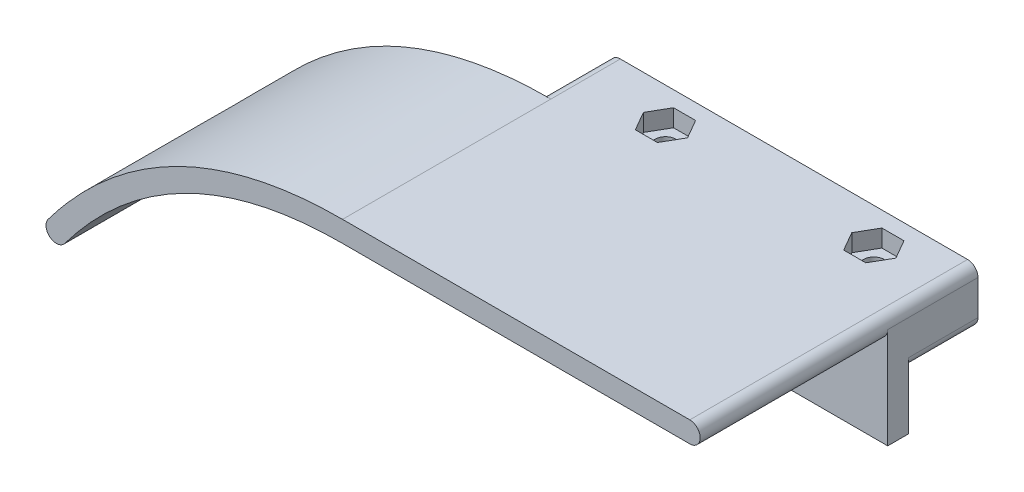
SolidWorks part; units mm, degrees
material "ABS"
ref_plane "前视基准面" through (0, 0, 0) normal (0, 0, 1) x (1, 0, 0)
ref_plane "上视基准面" through (0, 0, 0) normal (0, 1, 0) x (1, 0, 0)
ref_plane "右视基准面" through (0, 0, 0) normal (1, 0, 0) x (0, 0, -1)
sketch "草图1" plane through (0, 0, 0) normal (0, 0, 1) x (1, 0, 0)
  line L0 (-25, -1.5) -> (-50, -1.5) construction
  line L1 (-25, -1.5) -> (25, -1.5)
  line L2 (-25, -1.5) -> (-25, 1.5) construction
  line L4 (25, -1.5) -> (25, 1.5) construction
  line L5 (-25, -1.5) -> (25, 1.5) construction
  line L6 (-25, 1.5) -> (25, -1.5) construction
  line L7 (-50, -1.5) -> (-65, -21.5) construction
  line L8 (-25, 1.5) -> (25, 1.5)
  arc A0 (25, 1.5) -> (25, -1.5) centre (25, 0) cw
  arc A2 (-67.4, -19.7) -> (-65, -21.5) centre (-66.2, -20.6) ccw
  spline S0 degree 2 poles (-25, -1.5) (-50, -1.5) (-65, -21.5) knots 0 0 0 1 1 1
  spline S1 degree 1 poles (-25, 1.5) (-67.4, -19.7) knots 0 0 1 1 construction
  spline S2 degree 2 poles (-25, 1.5) (-34.8412, 1.5115) (-49.0088, -3.4823) (-61.5045, -11.8201) (-67.4, -19.7) knots 0 0 0 0.375 0.625 1 1 1
  point P0 (0, 0)
  dimension "D3" = 20
  dimension "D1" = 50
  dimension "D2" = 3
  dimension "D4" = 25
  dimension "D5" = 40
extrude "凸台-拉伸1" add sketch "草图1" along normal blind 30 contours L8 A0 L1 S0 A2 S2
sketch "草图2" plane through (0, 0, 0) normal (0, 0, -1) x (-1, 0, 0)
  line L0 (25, 1.5) -> (-25, 1.5) construction
  line L1 (25, 1.5) -> (-25, 1.5)
  line L2 (-26.5, 0) -> (-26.5, -22.1)
  line L3 (66.2, -22.1) -> (-26.5, -22.1)
  arc A0 (65, -21.5) -> (67.4, -19.7) centre (66.2, -20.6) ccw construction
  arc A1 (-25, 1.5) -> (-25, -1.5) centre (-25, 0) ccw construction
  arc A2 (66.2, -22.1) -> (67.4, -19.7) centre (66.2, -20.6) ccw
  arc A3 (-25, 1.5) -> (-26.5, 0) centre (-25, 0) ccw
  spline S0 degree 2 poles (-1644.9856, -2478.1381) (-209.195, 87.5308) (49.0088, -3.4823) (276.7427, -155.4382) (-914.3307, -2843.4975) knots -10.765594 -10.765594 -10.765594 0.375 0.625 11.765648 11.765648 11.765648 only from (25, 1.5) to (67.4, -19.7) construction
  spline S1 degree 2 poles (25, 1.5) (34.8412, 1.5115) (49.0088, -3.4823) (61.5045, -11.8201) (67.4, -19.7) knots 0 0 0 0.375 0.625 1 1 1
extrude "凸台-拉伸2" add sketch "草图2" against normal blind 3
sketch "草图3" plane through (0, 0, 0) normal (0, 0, -1) x (-1, 0, 0)
  line L0 (-25, 1.5) -> (25, 1.5)
  line L1 (-26.5, 0) -> (-26.5, -5)
  line L2 (-26.5, 0) -> (-26.5, -22.1) construction
  line L3 (26.5, 0) -> (26.5, -5)
  line L4 (-25, -6.5) -> (25, -6.5)
  arc A0 (-25, 1.5) -> (-26.5, 0) centre (-25, 0) ccw construction
  arc A1 (-26.5, -5) -> (-25, -6.5) centre (-25, -5) ccw
  arc A2 (25, -6.5) -> (26.5, -5) centre (25, -5) ccw
  arc A3 (26.5, 0) -> (25, 1.5) centre (25, 0) ccw
  arc A4 (-25, 1.5) -> (-26.5, 0) centre (-25, 0) ccw
  dimension "D1" = 8
extrude "凸台-拉伸3" add sketch "草图3" along normal blind 10
sketch "草图4" plane through (0, 1.5, 0) normal (0, 1, 0) x (1, 0, 0)
  line L0 (-25, 5) -> (-15.7274, 5) construction
  line L3 (-25, 10) -> (25, 10) construction
  line L4 (26.5, -3) -> (26.5, 10) construction
  circle A0 centre (-13.5, 5) radius 1.5
  circle A1 centre (16.5, 5) radius 1.5
  dimension "D1" = 5
  dimension "D2" = 3
  dimension "D3" = 30
  dimension "D4" = 10
extrude "切除-拉伸1" cut sketch "草图4" against normal through all contours A0 | A1
sketch "草图5" plane through (0, 0, 0) normal (0, 0, -1) x (-1, 0, 0)
  line L0 (-26.5, -14.5) -> (33.5, -14.5)
  line L1 (-26.5, -5) -> (-26.5, -22.1) construction
  line L2 (-26.5, -22.1) -> (66.2, -22.1) construction
  line L3 (-25, -6.5) -> (25, -6.5) construction
  line L4 (-26.5, -14.5) -> (-26.5, -22.1)
  line L5 (-26.5, -22.1) -> (41.1, -22.1)
  arc A0 (33.5, -14.5) -> (41.1, -22.1) centre (33.5, -22.1) cw
  dimension "D1" = 8
  dimension "D2" = 60
extrude "切除-拉伸2" cut sketch "草图5" against normal through all
sketch "草图6" plane through (0, 1.5, 0) normal (0, 1, 0) x (1, 0, 0)
  line L1 (-11.9123, 7.75) -> (-15.0877, 7.75)
  line L2 (-15.0877, 7.75) -> (-16.6754, 5)
  line L3 (-16.6754, 5) -> (-15.0877, 2.25)
  line L4 (-15.0877, 2.25) -> (-11.9123, 2.25)
  line L5 (-11.9123, 2.25) -> (-10.3246, 5)
  line L6 (-10.3246, 5) -> (-11.9123, 7.75)
  line L7 (18.0877, 7.75) -> (14.9123, 7.75)
  line L8 (14.9123, 7.75) -> (13.3246, 5)
  line L9 (13.3246, 5) -> (14.9123, 2.25)
  line L10 (14.9123, 2.25) -> (18.0877, 2.25)
  line L11 (18.0877, 2.25) -> (19.6754, 5)
  line L12 (19.6754, 5) -> (18.0877, 7.75)
  circle A0 centre (-13.5, 5) radius 2.75 construction
  circle A1 centre (16.5, 5) radius 2.75 construction
  dimension "D1" = 5.5
extrude "切除-拉伸3" cut sketch "草图6" along normal through all from offset 2.5 offset against normal yes
fillet "圆角1" radius 2 1 edges at (-41.1, -22.1, 1.5)
